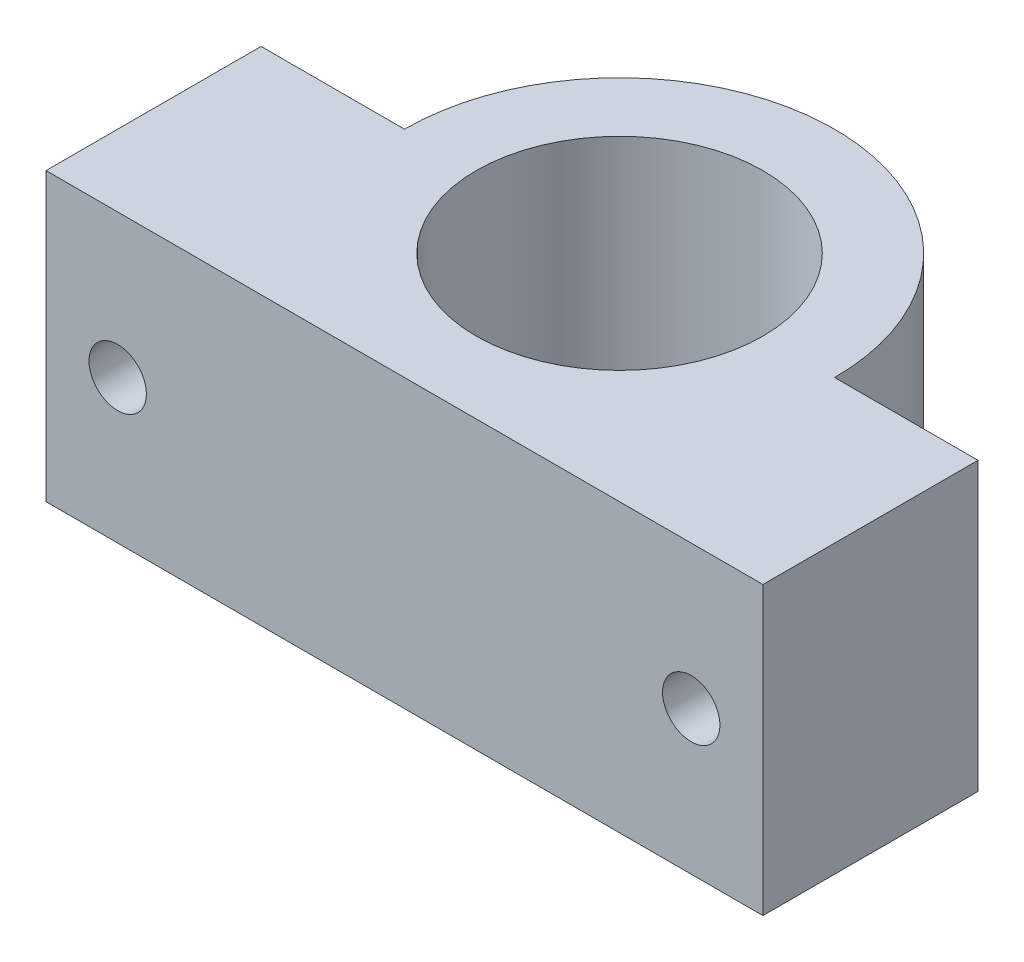
SolidWorks part; units mm, degrees
ref_plane "Front Plane" through (0, 0, 0) normal (0, 0, 1) x (1, 0, 0)
ref_plane "Top Plane" through (0, 0, 0) normal (0, 1, 0) x (1, 0, 0)
ref_plane "Right Plane" through (0, 0, 0) normal (1, 0, 0) x (0, 0, -1)
sketch "Sketch2" plane through (0, 0, 0) normal (0, 1, 0) x (1, 0, 0)
  line L0 (-50, 0) -> (0, 0)
  line L1 (0, 0) -> (0, 15)
  line L2 (0, 15) -> (-10, 15)
  line L3 (-40, 15) -> (-50, 15)
  line L4 (-50, 15) -> (-50, 0)
  arc A0 (-10, 15) -> (-40, 15) centre (-25, 15) ccw
  dimension "D1" = 15
  dimension "D2" = 50
  dimension "D3" = 10
  dimension "D4" = 15
extrude "Boss-Extrude1" add sketch "Sketch2" along normal blind 20
sketch "Sketch3" plane through (0, 0, 0) normal (0, -1, 0) x (-1, 0, 0)
  circle A0 centre (25, 15) radius 10
  dimension "D1" = 20
extrude "Cut-Extrude1" cut sketch "Sketch3" against normal through all
sketch "Sketch4" plane through (0, 0, -15) normal (0, 0, -1) x (-1, 0, 0)
  line L0 (45, 0) -> (45, 20) construction
  line L1 (40, 0) -> (50, 0) construction
  line L2 (40, 20) -> (50, 20) construction
  line L3 (5, 0) -> (5, 20) construction
  line L4 (0, 0) -> (10, 0) construction
  line L5 (0, 20) -> (10, 20) construction
  circle A0 centre (45, 10) radius 2
  circle A1 centre (5, 10) radius 2
  dimension "D1" = 4
  dimension "D2" = 4
extrude "Cut-Extrude2" cut sketch "Sketch4" against normal through all
